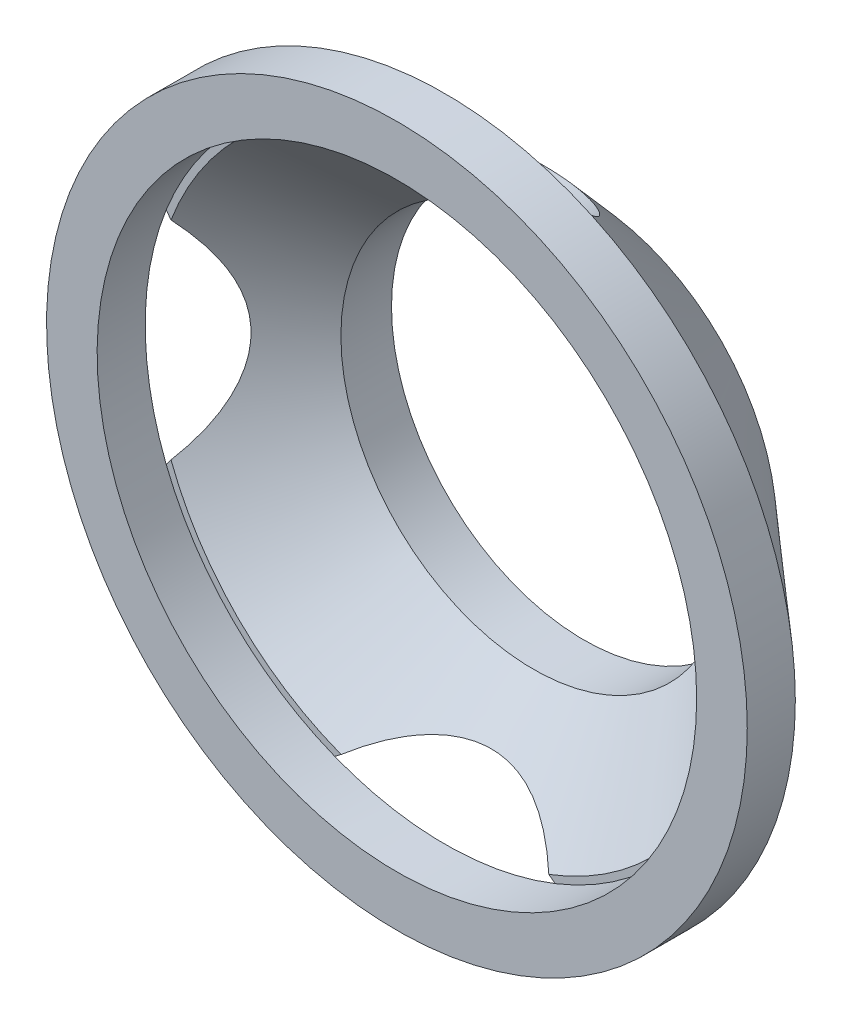
SolidWorks part; units mm, degrees
ref_plane "Front Plane" through (0, 0, 0) normal (0, 0, 1) x (1, 0, 0)
ref_plane "Top Plane" through (0, 0, 0) normal (0, 1, 0) x (1, 0, 0)
ref_plane "Right Plane" through (0, 0, 0) normal (1, 0, 0) x (0, 0, -1)
sketch "Sketch1" plane through (0, 0, 0) normal (0, 0, 1) x (1, 0, 0)
  circle A2 centre (0, 0) radius 11.85
  circle A3 centre (0, 0) radius 13.85
  circle A4 centre (0, 0) radius 11.85 construction
  circle A5 centre (0, 0) radius 13.85 construction
extrude "Boss-Extrude1" add sketch "Sketch1" along normal blind 1.9
sketch "Sketch2" plane through (0, 0, 0) normal (0, 1, 0) x (1, 0, 0)
  line L0 (-13.85, 0) -> (-7.6136, 5.5)
  line L1 (7.6136, 5.5) -> (-7.6136, 5.5) construction
  line L3 (13.85, 0) -> (-13.85, 0) construction
  line L4 (-7.6136, 3.5) -> (-11.5822, 0)
  line L5 (-7.6136, 3.5) -> (0, 3.5)
  line L7 (-13.85, 0) -> (-11.5822, 0)
  line L8 (-7.6136, 5.5) -> (0, 5.5)
  line L9 (0, 5.5) -> (0, 3.5)
  point P2 (-9.9077, 2.9252)
  point P6 (0, 5.5)
  dimension "D1" = 2
  dimension "D2" = 5.5
  dimension "D3" = 1.5
revolve "Revolve1" add sketch "Sketch2" angle 360 about L9
sketch "Sketch4" plane through (0, 0, -5.5) normal (0, 0, -1) x (-1, 0, 0)
  line L0 (-9.5, 0) -> (9.5, 0) construction
  line L1 (0, -9.5) -> (0, 9.5) construction
  circle A0 centre (0, 16.5) radius 7
  circle A1 centre (16.5, 0) radius 7
  circle A2 centre (0, -16.5) radius 7
  circle A4 centre (-16.5, 0) radius 7 [skipped]
  point P4 (0, 0)
  point P8 (0, 0)
  point P18 (0, 0)
  circle M3 centre (0, 0) radius 7.6136
  dimension "D3" = 14
  dimension "D1" = 19
  dimension "D2" = 19
  dimension "D4" = 4
extrude "Cut-Extrude2" cut sketch "Sketch4" against normal blind 5.5 contours A1 M3 | A1 M3 | A2 M3 | A2 M3 | A0
ref_plane "Plane2" through (0, 0, -5.5) normal (0, 0, 1) x (1, 0, 0)
sketch "Sketch5" plane through (0, 0, -5.5) normal (0, 0, 1) x (1, 0, 0)
  circle A1 centre (0, 0) radius 7
  point P0 (0, 0)
  point P2 (0, 0)
  point P9 (-9.5, 0)
  point P10 (9.5, 0)
  dimension "D2" = 14
extrude "Cut-Extrude3" [suppressed] cut sketch "Sketch5" against normal blind 2
sketch "Sketch6" plane through (0, 0, -5.5) normal (0, 0, -1) x (-1, 0, 0)
  circle A0 centre (0, 0) radius 6.6675
  dimension "D1" = 13.335
sketch "Sketch7" plane through (0, 0, -3.3882) normal (0, 0, 1) x (1, 0, 0)
  circle A0 centre (0, 0) radius 8.5
  dimension "D1" = 17
extrude "Boss-Extrude2" [suppressed] add sketch "Sketch7" along normal blind 6
extrude "Cut-Extrude5" [suppressed] cut sketch "Sketch6" against normal through all
sketch "Sketch8" [suppressed] plane through (0, 0, -5.5) normal (0, 0, -1) x (-1, 0, 0)
  circle A0 centre (0, 0) radius 2.3813
  circle A1 centre (0, 0) radius 6.6675 construction
  circle A2 centre (0, 0) radius 6.6675
  dimension "D1" = 4.7625
hole_wizard "#33 (0.113) Diameter Hole1" [suppressed] positions "Sketch9" profile "Sketch10" hole size "#33" standard "ANSI Inch"
sketch "Sketch9" [suppressed] plane through (0, 0, -5.5) normal (0, 0, -1) x (-1, 0, 0)
  line L0 (-7.7782, 7.7782) -> (7.7782, -7.7782) construction
  line L2 (-7.7782, -7.7782) -> (7.7782, 7.7782) construction
  line L4 (0, 0) -> (0, -6.6675) construction
  circle A0 centre (0, 0) radius 6.6675 construction
  point P0 (7.7782, 7.7782)
  point P2 (7.7782, -7.7782)
  point P4 (-7.7782, -7.7782)
  point P6 (-7.7782, 7.7782)
  dimension "D1" = 90
  dimension "D2" = 11
  dimension "D3" = 45
sketch "Sketch10" plane through (-7.7782, 7.7782, -5.5) normal (1, 0, 0) x (0, 1, 0)
  line L0 (0, 0) -> (0, 7.4)
  line L1 (0, 7.4) -> (1.4351, 7.4)
  line L2 (1.4351, 7.4) -> (1.4351, 0)
  line L5 (1.4351, 0) -> (0, 0)
  line L11 (0, -6.35) -> (0, 107.95) construction
  dimension "Thru Hole Dia." = 2.8702
  dimension "Thru Hole Depth" = 7.4
